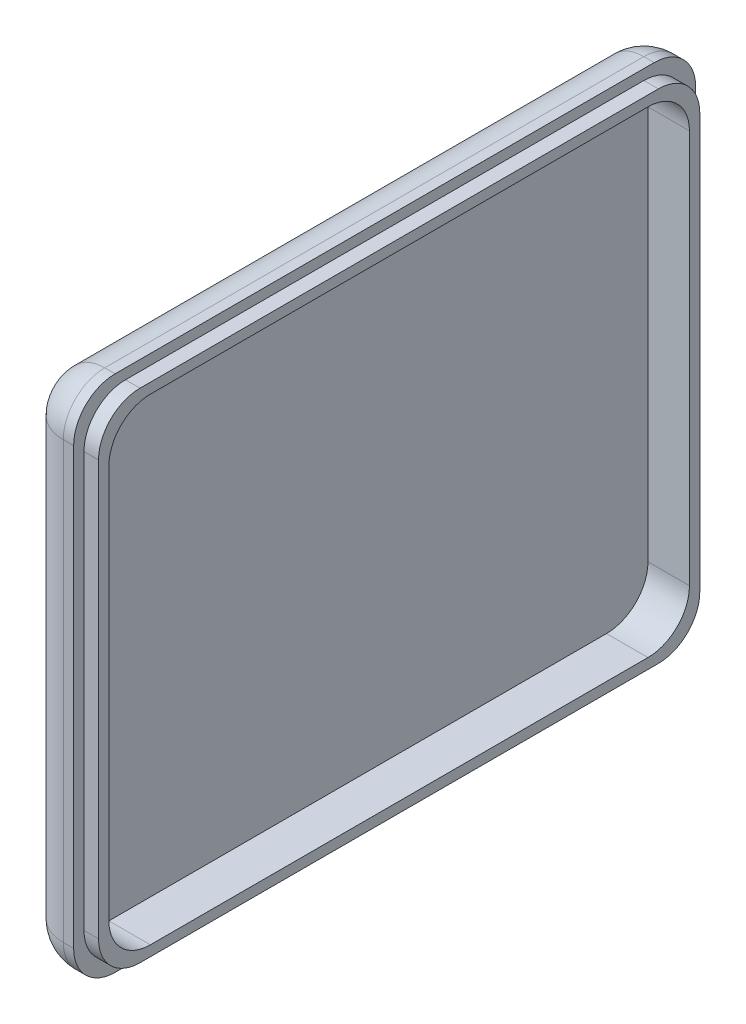
SolidWorks part; units mm, degrees
ref_plane "Front Plane" through (0, 0, 0) normal (0, 0, 1) x (1, 0, 0)
ref_plane "Top Plane" through (0, 0, 0) normal (0, 1, 0) x (1, 0, 0)
ref_plane "Right Plane" through (0, 0, 0) normal (1, 0, 0) x (0, 0, -1)
sketch "Sketch5" plane through (0, 0, 0) normal (1, 0, 0) x (0, 0, -1)
  line L1 (27.7707, 63.5) -> (103.9707, 63.5)
  line L2 (27.7707, 63.5) -> (27.7707, 0)
  line L3 (27.7707, 0) -> (103.9707, 0)
  line L4 (103.9707, 63.5) -> (103.9707, 0)
  dimension "D1" = 63.5
  dimension "D2" = 76.2
extrude "Boss-Extrude2" add sketch "Sketch5" along normal blind 6.35
sketch "Sketch6" plane through (6.35, 0, 0) normal (1, 0, 0) x (0, 0, -1)
  line L0 (103.9707, 0) -> (103.9707, 63.5) construction
  line L1 (29.0407, 62.23) -> (102.7007, 62.23)
  line L2 (29.0407, 62.23) -> (29.0407, 1.27)
  line L3 (29.0407, 1.27) -> (102.7007, 1.27)
  line L4 (102.7007, 62.23) -> (102.7007, 1.27)
  line L5 (103.9707, 63.5) -> (27.7707, 63.5) construction
  line L6 (27.7707, 63.5) -> (27.7707, 0) construction
  line L7 (27.7707, 0) -> (103.9707, 0) construction
  dimension "D1" = 1.27
  dimension "D2" = 1.27
  dimension "D3" = 1.27
  dimension "D4" = 1.27
extrude "Boss-Extrude3" add sketch "Sketch6" along normal blind 1.778
sketch "Sketch7" plane through (8.128, 0, 0) normal (1, 0, 0) x (0, 0, -1)
  line L0 (29.0407, 62.23) -> (29.0407, 1.27) construction
  line L1 (30.3107, 60.96) -> (101.4307, 60.96)
  line L2 (30.3107, 60.96) -> (30.3107, 2.54)
  line L3 (30.3107, 2.54) -> (101.4307, 2.54)
  line L4 (101.4307, 60.96) -> (101.4307, 2.54)
  line L5 (102.7007, 62.23) -> (29.0407, 62.23) construction
  line L6 (102.7007, 1.27) -> (102.7007, 62.23) construction
  line L7 (29.0407, 1.27) -> (102.7007, 1.27) construction
  dimension "D1" = 1.27
  dimension "D2" = 1.27
  dimension "D3" = 1.27
  dimension "D4" = 1.27
extrude "Cut-Extrude2" cut sketch "Sketch7" against normal blind 5.08
fillet "Fillet7" radius 5.08 2 edges at (5.588, 2.54, -30.3107) (5.588, 2.54, -101.4307)
fillet "Fillet8" radius 5.08 2 edges at (5.588, 60.96, -30.3107) (5.588, 60.96, -101.4307)
fillet "Fillet9" radius 5.08 1 edges at (7.239, 1.27, -29.0407)
fillet "Fillet10" radius 5.08 1 edges at (3.175, 0, -27.7707)
fillet "Fillet11" radius 5.08 4 edges at (3.175, 63.5, -103.9707) (7.239, 62.23, -102.7007) (3.175, 0, -103.9707) (7.239, 1.27, -102.7007)
fillet "Fillet12" radius 5.08 2 edges at (3.175, 63.5, -27.7707) (7.239, 62.23, -29.0407)
fillet "Fillet13" radius 5.08 8 edges at (0, 62.0121, -29.2586) (0, 62.0121, -102.4828) (0, 1.4879, -102.4828) (0, 1.4879, -29.2586) (0, 63.5, -65.8707) (0, 31.75, -103.9707) (0, 0, -65.8707) (0, 31.75, -27.7707)
